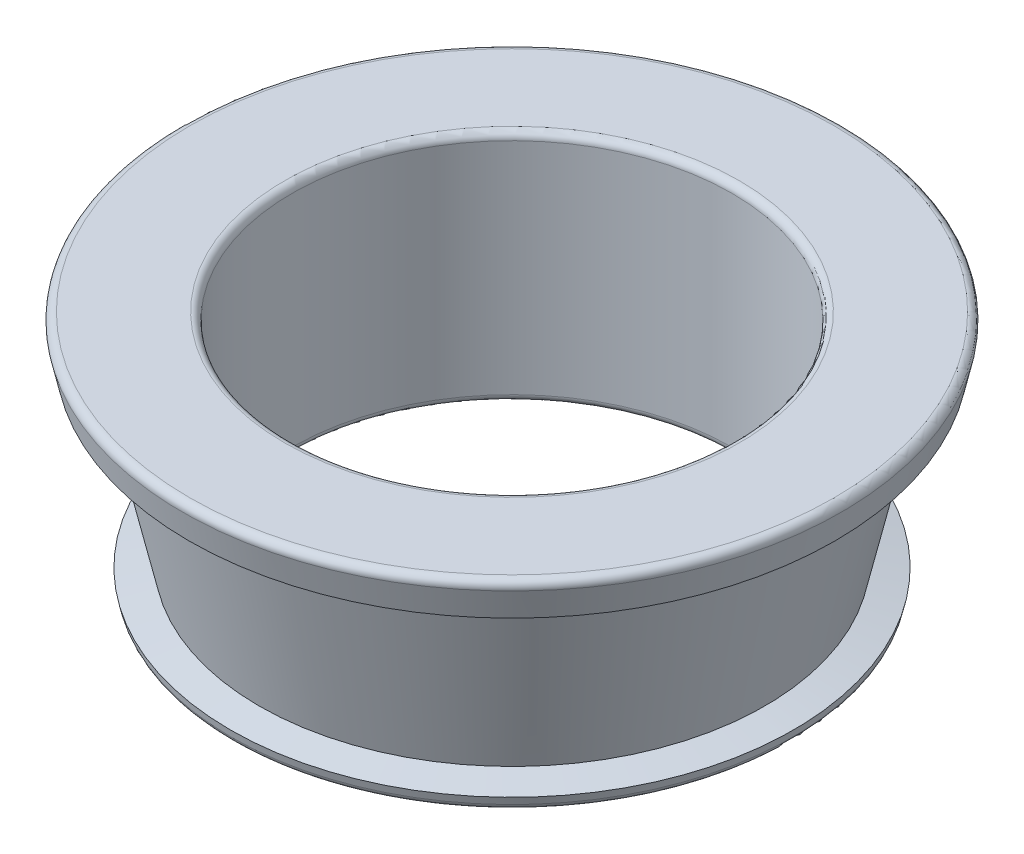
SolidWorks part; units mm, degrees
ref_plane "Ön Düzlem" through (0, 0, 0) normal (0, 0, 1) x (1, 0, 0)
ref_plane "Üst Düzlem" through (0, 0, 0) normal (0, 1, 0) x (1, 0, 0)
ref_plane "Sağ Düzlem" through (0, 0, 0) normal (1, 0, 0) x (0, 0, -1)
sketch "Çizim1" plane through (0, 0, 0) normal (0, 0, 1) x (1, 0, 0)
  line L0 (0, 0.5) -> (0, 15.5)
  line L1 (-0.5, 16) -> (-6.975, 16)
  line L2 (-7.4628, 15.3902) -> (-7.0332, 13.4811)
  line L3 (-3.6, 0) -> (-0.5, 0)
  line L4 (-5.082, 13.9201) -> (-2.2514, 1.3393)
  line L5 (-2.2514, 1.3393) -> (-4.2026, 0.9003)
  line L6 (15, 1.3393) -> (15, 18.8055) construction
  line L7 (-7.0332, 13.4811) -> (-5.082, 13.9201)
  line L8 (-4.2026, 0.9003) -> (-4.0878, 0.3902)
  arc A0 (-6.975, 16) -> (-7.4628, 15.3902) centre (-6.975, 15.5) ccw
  arc A1 (0, 0.5) -> (-0.5, 0) centre (-0.5, 0.5) cw
  arc A2 (0, 15.5) -> (-0.5, 16) centre (-0.5, 15.5) ccw
  arc A3 (-4.0878, 0.3902) -> (-3.6, 0) centre (-3.6, 0.5) ccw
  point P11 (-7.6, 16)
  point P14 (0, 0)
  point P17 (0, 16)
  point P20 (-4, 0)
  dimension "D5" = 0.5
  dimension "D6" = 0.5
  dimension "D1" = 7.6
  dimension "D2" = 16
  dimension "D3" = 4
  dimension "D4" = 2
  dimension "D7" = 15
revolve "Döndür1" add sketch "Çizim1" angle 360 about L6
